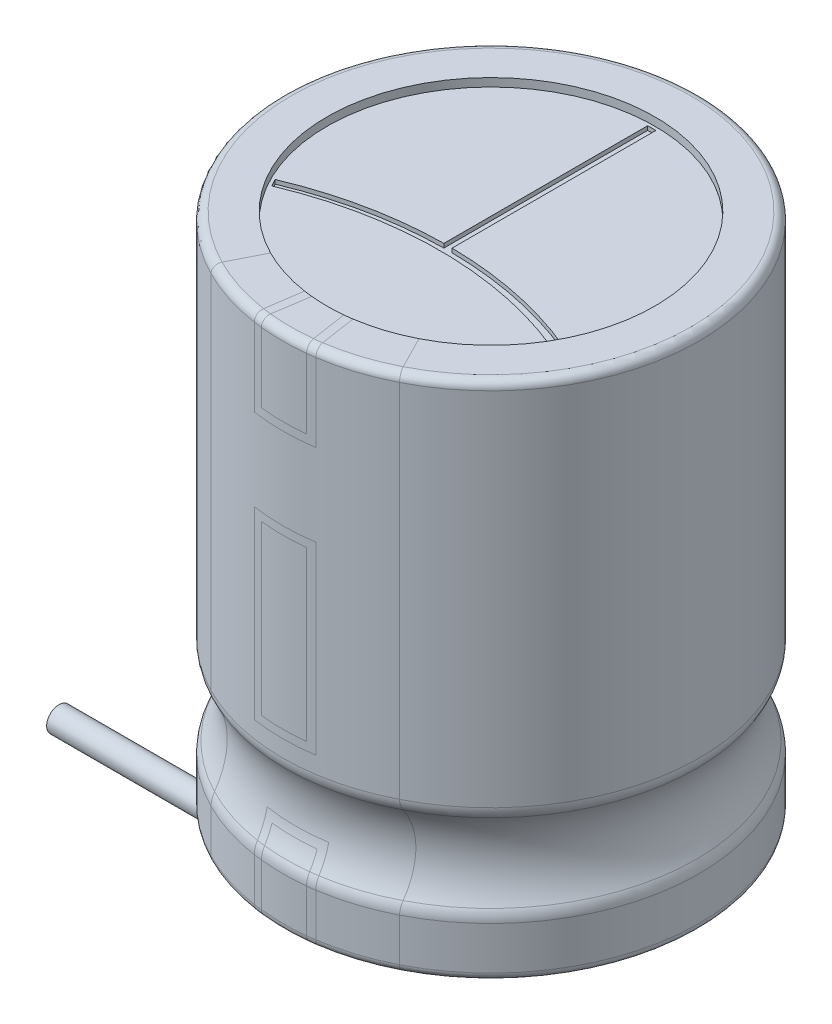
SolidWorks part; units mm, degrees
ref_plane "Płaszczyzna przednia" through (0, 0, 0) normal (0, 0, 1) x (1, 0, 0)
ref_plane "Płaszczyzna górna" through (0, 0, 0) normal (0, 1, 0) x (1, 0, 0)
ref_plane "Płaszczyzna prawa" through (0, 0, 0) normal (1, 0, 0) x (0, 0, -1)
sketch "Szkic1" plane through (0, 0, 0) normal (1, 0, 0) x (0, 0, -1)
  line L0 (0, 0) -> (4.88, 0)
  line L1 (5.08, 0.2) -> (5.08, 1.2475)
  line L2 (4.88, 12.7) -> (0, 12.7)
  line L3 (0, 12.7) -> (0, 0)
  line L6 (5.08, 3.6925) -> (5.08, 12.5)
  arc A0 (5.0042, 3.4279) -> (5.0042, 1.5121) centre (6.54, 2.47) ccw
  arc A1 (5.08, 1.2475) -> (5.0042, 1.5121) centre (4.58, 1.2475) ccw
  arc A2 (5.08, 3.6925) -> (5.0042, 3.4279) centre (4.58, 3.6925) cw
  arc A3 (5.08, 12.5) -> (4.88, 12.7) centre (4.88, 12.5) ccw
  arc A4 (4.88, 0) -> (5.08, 0.2) centre (4.88, 0.2) ccw
  point P14 (5.08, 12.7)
  point P17 (5.08, 0)
  dimension "D6" = 1.2475
  dimension "D4" = 4.58
  dimension "D5" = 5.0042
  dimension "D3" = 0.2
  dimension "D1" = 1.81
  dimension "D2" = 0.5
  dimension "D11" = 12.7
revolve "Obrót1" add sketch "Szkic1" angle 360 about L3
sketch "Szkic2" plane through (0, 12.7, 0) normal (0, 1, 0) x (1, 0, 0)
  circle A0 centre (0, 0) radius 4
  dimension "D1" = 8
extrude "Wytnij-wyciągnięcie1" cut sketch "Szkic2" against normal blind 0.2
sketch "Szkic3" plane through (0, 0, 0) normal (0, -1, 0) x (1, 0, 0)
  circle A0 centre (0, 0) radius 4
  dimension "D1" = 8
extrude "Wytnij-wyciągnięcie2" cut sketch "Szkic3" against normal blind 0.8
sketch "Szkic4" plane through (0, 12.5, 0) normal (0, 1, 0) x (1, 0, 0)
  line L0 (-0.1, 3.9219) -> (-0.1, -1.0496)
  line L2 (0.1, 3.9219) -> (0.1, -1.0496)
  circle A1 centre (0, 0) radius 4 construction
  arc A3 (-3.5075, -1.7573) -> (-3.413, -1.9345) centre (0, 0) ccw
  arc A5 (0.1, 3.9219) -> (-0.1, 3.9219) centre (0, 0) ccw
  arc A6 (0.1, -1.0496) -> (3.5075, -1.7573) centre (0, -10.088) cw
  arc A7 (-0.1, -1.0496) -> (-3.5075, -1.7573) centre (0, -10.088) ccw
  arc A8 (0, -1.249) -> (3.413, -1.9345) centre (0, -10.088) cw
  arc A9 (0, -1.249) -> (-3.413, -1.9345) centre (0, -10.088) ccw
  arc A10 (3.413, -1.9345) -> (3.5075, -1.7573) centre (0, 0) ccw
  dimension "D1" = 3.9231
  dimension "D2" = 9.039
  dimension "D3" = 8.839
  dimension "D4" = 0.1
  dimension "D7" = 1.0496
extrude "Wytnij-wyciągnięcie3" cut sketch "Szkic4" against normal blind 0.1
sketch "Szkic5" plane through (0, 0, 0) normal (0, 0, 1) x (1, 0, 0)
  line L0 (0, 0) -> (2.3, 0)
  line L1 (2.3, 0) -> (2.3, 12.7)
  line L2 (2.3, 12.7) -> (-2.3, 12.7)
  line L3 (-2.3, 12.7) -> (-2.3, 0)
  line L4 (-2.3, 0) -> (0, 0)
  line L5 (-0.55, 4.3) -> (-0.55, 8.4)
  line L6 (-0.55, 8.4) -> (0.55, 8.4)
  line L9 (-0.75, 12.7) -> (-0.75, 10.6)
  line L10 (-0.75, 10.6) -> (0.75, 10.6)
  line L11 (-0.75, 4.1) -> (0.75, 4.1)
  line L12 (-0.75, 4.1) -> (-0.75, 8.6)
  line L13 (-0.75, 8.6) -> (0.75, 8.6)
  line L14 (0.75, 4.1) -> (0.75, 8.6)
  line L15 (0.75, 10.6) -> (0.75, 12.7)
  line L16 (-0.75, 0) -> (-0.75, 2.1)
  line L17 (-0.75, 2.1) -> (0.75, 2.1)
  line L18 (0.75, 2.1) -> (0.75, 0)
  line L19 (0.55, 4.3) -> (0.55, 8.4)
  line L20 (-0.55, 4.3) -> (0.55, 4.3)
  line L21 (-0.55, 12.7) -> (-0.55, 10.8)
  line L22 (-0.55, 10.8) -> (0.55, 10.8)
  line L23 (0.55, 10.8) -> (0.55, 12.7)
  line L24 (-0.55, 0) -> (-0.55, 1.9)
  line L25 (-0.55, 1.9) -> (0.55, 1.9)
  line L26 (0.55, 1.9) -> (0.55, 0)
  dimension "D1" = 0.55
  dimension "D2" = 0.75
  dimension "D3" = 2.3
  dimension "D4" = 0.55
  dimension "D5" = 0.75
  dimension "D6" = 1.9
  dimension "D7" = 2.1
  dimension "D8" = 4.1
  dimension "D9" = 4.3
  dimension "D10" = 8.4
  dimension "D11" = 8.6
  dimension "D12" = 10.6
split line "Linia podziałowa1"
sketch "Szkic7" plane through (0, 0, 0) normal (0, 1, 0) x (1, 0, 0)
  line L2 (-2.3, -4.5295) -> (-1.811, -3.5665)
  line L3 (-0.5516, -5.05) -> (-0.392, -3.9807)
  line L6 (-0.75, -5.0243) -> (-0.5906, -3.9562)
  line L7 (0.75, -5.0243) -> (0.5906, -3.9562)
  line L8 (1.811, -3.5665) -> (2.3, -4.5295)
  line L9 (0.5516, -5.05) -> (0.392, -3.9807)
  arc A0 (-2.3, -4.5295) -> (2.3, -4.5295) centre (0, 0) ccw
  arc A1 (-1.811, -3.5665) -> (1.811, -3.5665) centre (0, 0) ccw
  dimension "D1" = 5.08
  dimension "D2" = 4
  dimension "D3" = 0.392
  dimension "D4" = 0.5516
  dimension "D5" = 0.75
  dimension "D6" = 1.811
split line "Linia podziałowa2"
sketch "Szkic12" plane through (0, 0.8, 0) normal (0, -1, 0) x (-1, 0, 0)
  line L1 (0, 0) -> (0, -2.54) construction
  line L2 (1, -2.54) -> (1, -3.1957)
  line L3 (-1, -2.54) -> (-1, -3.1957)
  line L4 (3.3974, -0.3) -> (-3.3974, -0.3)
  arc A0 (1.413, -3.4736) -> (3.6929, -0.6522) centre (0, 0) ccw
  arc A1 (1, -2.54) -> (-1, -2.54) centre (0, -2.54) ccw
  arc A2 (-3.6929, -0.6522) -> (-1.413, -3.4736) centre (0, 0) ccw
  arc A3 (-1, -3.1957) -> (-1.413, -3.4736) centre (-1.3, -3.1957) cw
  arc A4 (1, -3.1957) -> (1.413, -3.4736) centre (1.3, -3.1957) ccw
  arc A5 (-3.6929, -0.6522) -> (-3.3974, -0.3) centre (-3.3974, -0.6) cw
  arc A6 (3.6929, -0.6522) -> (3.3974, -0.3) centre (3.3974, -0.6) ccw
  circle A7 centre (0, 0) radius 4 construction
  dimension "D1" = 3.75
  dimension "D2" = 0.3
  dimension "D3" = 1
  dimension "D4" = 3.3974
  dimension "D5" = 2.54
extrude "Dodanie-wyciągnięcie3" add sketch "Szkic12" along normal blind 1.2
pattern_circular "Szyk kołowy1" count 2 over 360 about axis through (0, 0, 0) along (0, 1, 0) of "Dodanie-wyciągnięcie3"
sketch "Szkic13" plane through (0, -0.4, 0) normal (0, -1, 0) x (-1, 0, 0)
  circle A0 centre (0, 0) radius 3
  circle A1 centre (0, 0) radius 2.5
  dimension "D1" = 6
  dimension "D2" = 5
extrude "Wytnij-wyciągnięcie4" cut sketch "Szkic13" against normal blind 0.6
sketch "Szkic11" plane through (0, 0.8, 0) normal (0, -1, 0) x (-1, 0, 0)
  line L0 (0, 0) -> (0, -2.54) construction
  line L1 (0, 0) -> (0, 2.54) construction
  circle A0 centre (0, -2.54) radius 0.3
  circle A1 centre (0, 2.54) radius 0.3
  dimension "D3" = 0.6
  dimension "D4" = 0.6
  dimension "D1" = 2.54
  dimension "D2" = 2.54
sketch "Эскиз1" plane through (0, 0, 0) normal (0, 0, 1) x (1, 0, 0)
  line L0 (0, 0.8) -> (0, 0.25)
  line L1 (-0.3, 0.8) -> (0.3, 0.8) construction
  line L2 (-1, -0.75) -> (-8, -0.75)
  arc A0 (-1, -0.75) -> (0, 0.25) centre (-1, 0.25) ccw
  dimension "D3" = 1
  dimension "D1" = 8
  dimension "D2" = 0.75
sweep "По траектории2" add profiles "Szkic11" path "Эскиз1"
